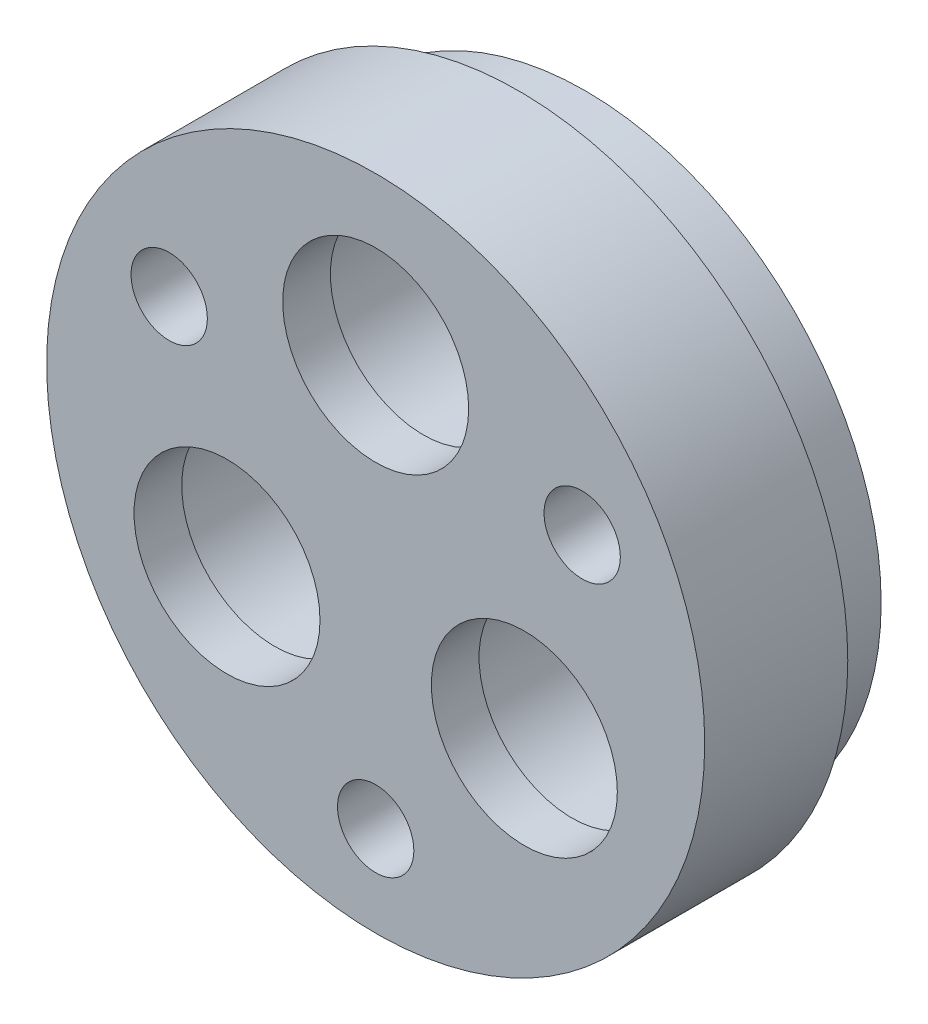
SolidWorks part; units mm, degrees
ref_plane "Plan de face" through (0, 0, 0) normal (0, 0, 1) x (1, 0, 0)
ref_plane "Plan de dessus" through (0, 0, 0) normal (0, 1, 0) x (1, 0, 0)
ref_plane "Plan de droite" through (0, 0, 0) normal (1, 0, 0) x (0, 0, -1)
sketch "Esquisse1" plane through (0, 0, 0) normal (0, 0, 1) x (1, 0, 0)
  line L0 (0, 0) -> (0, 15.3035) construction
  circle A0 centre (0, 0) radius 34.5
  dimension "D1" = 69
extrude "Boss.-Extru.1" add sketch "Esquisse1" along normal blind 15
sketch "Esquisse2" plane through (0, 0, 15) normal (0, 0, 1) x (1, 0, 0)
  line L0 (0, 0) -> (0, 18) construction
  line L1 (0, 0) -> (15.5885, -9) construction
  line L2 (0, 0) -> (-15.5885, -9) construction
  circle A0 centre (0, 18) radius 10.8
  circle A1 centre (15.5885, -9) radius 10.8
  circle A2 centre (-15.5885, -9) radius 10.8
  dimension "D2" = 21.6
  dimension "D1" = 18
  dimension "D3" = 3
extrude "Enlèv. mat.-Extru.1" cut sketch "Esquisse2" against normal blind 15
sketch "Esquisse3" plane through (0, 0, 15) normal (0, 0, 1) x (1, 0, 0)
  circle A0 centre (0, 18) radius 11
  circle A1 centre (0, 18) radius 9.75
  circle A2 centre (15.5885, -9) radius 9.75
  circle A3 centre (15.5885, -9) radius 11
  circle A4 centre (-15.5885, -9) radius 9.75
  circle A5 centre (-15.5885, -9) radius 11
  point P13 (0, 0)
  dimension "D1" = 22
  dimension "D2" = 19.5
  dimension "D3" = 3
extrude "Boss.-Extru.2" add sketch "Esquisse3" against normal blind 5
sketch "Esquisse4" plane through (0, 0, 15) normal (0, 0, 1) x (1, 0, 0)
  line L0 (0, 0) -> (0, -21) construction
  line L1 (0, 0) -> (-18.1865, 10.5) construction
  line L2 (0, 0) -> (18.1865, 10.5) construction
  circle A2 centre (21.6506, 12.5) radius 4
  circle A3 centre (-21.6506, 12.5) radius 4
  circle A4 centre (0, -25) radius 4
  dimension "D2" = 8
  dimension "D3" = 25
  dimension "D1" = 3
extrude "Enlèv. mat.-Extru.2" cut sketch "Esquisse4" against normal through all
sketch "Esquisse6" plane through (0, 0, 0) normal (0, 0, -1) x (-1, 0, 0)
  circle A0 centre (0, -25) radius 4 construction
  circle A1 centre (-15.5885, -9) radius 10.8 construction
  circle A2 centre (0, 18) radius 10.8 construction
  circle A3 centre (15.5885, -9) radius 10.8 construction
  circle A4 centre (21.6506, 12.5) radius 4 construction
  circle A5 centre (-21.6506, 12.5) radius 4 construction
  circle A6 centre (0, -25) radius 4
  circle A7 centre (-15.5885, -9) radius 10.8
  circle A8 centre (0, 18) radius 10.8
  circle A9 centre (15.5885, -9) radius 10.8
  circle A10 centre (21.6506, 12.5) radius 4
  circle A11 centre (-21.6506, 12.5) radius 4
  circle A12 centre (0, 0) radius 31
  dimension "D1" = 62
extrude "Boss.-Extru.5" add sketch "Esquisse6" along normal blind 7
